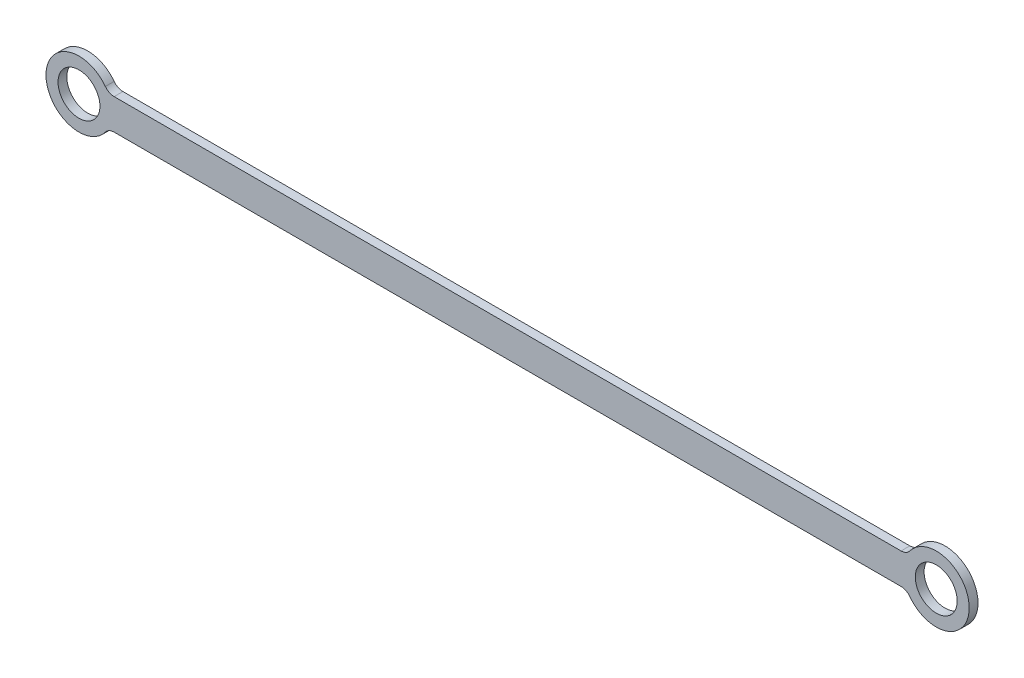
SolidWorks part; units mm, degrees
ref_plane "前视基准面" through (0, 0, 0) normal (0, 0, 1) x (1, 0, 0)
ref_plane "上视基准面" through (0, 0, 0) normal (0, 1, 0) x (1, 0, 0)
ref_plane "右视基准面" through (0, 0, 0) normal (1, 0, 0) x (0, 0, -1)
sketch "草图2" plane through (0, 0, 0) normal (0, 0, 1) x (1, 0, 0)
  line L0 (-179, 7) -> (179, 7)
  line L1 (179, -7) -> (-179, -7)
  circle A0 centre (-195, 0) radius 9.53
  circle A1 centre (195, 0) radius 9.53
  circle A2 centre (195, 0) radius 15 construction
  circle A3 centre (-195, 0) radius 15 construction
  arc A4 (183, -9) -> (183, 9) centre (195, 0) ccw
  arc A5 (-183, -9) -> (-183, 9) centre (-195, 0) cw
  arc A6 (-179, 7) -> (-183, 9) centre (-179, 12) cw
  arc A7 (-179, -7) -> (-183, -9) centre (-179, -12) ccw
  arc A8 (183, -9) -> (179, -7) centre (179, -12) ccw
  arc A9 (183, 9) -> (179, 7) centre (179, 12) cw
  dimension "D1" = 5
extrude "凸台-拉伸2" add sketch "草图2" along normal blind 4
